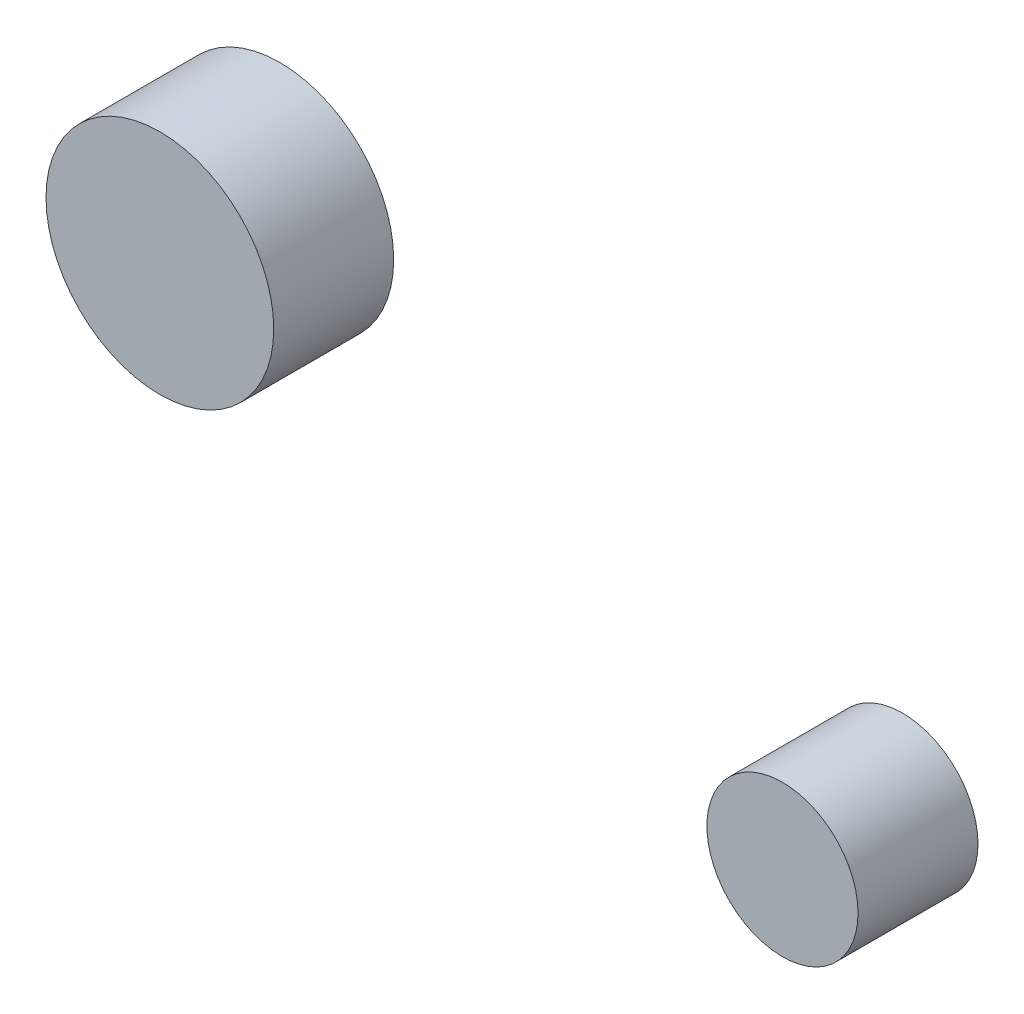
SolidWorks part; units mm, degrees
ref_plane "Front Plane" through (0, 0, 0) normal (0, 0, 1) x (1, 0, 0)
ref_plane "Top Plane" through (0, 0, 0) normal (0, 1, 0) x (1, 0, 0)
ref_plane "Right Plane" through (0, 0, 0) normal (1, 0, 0) x (0, 0, -1)
sketch "CurveSketch" plane through (0, 0, 0) normal (0, 0, 1) x (1, 0, 0)
  circle A0 centre (-31.719, 7.193) radius 11.137
  circle A1 centre (29.173, -13.719) radius 7.391
  dimension "D1" = 11.137
  dimension "D2" = 7.391
extrude "CurveBoss" add sketch "CurveSketch" along normal blind 11.731
